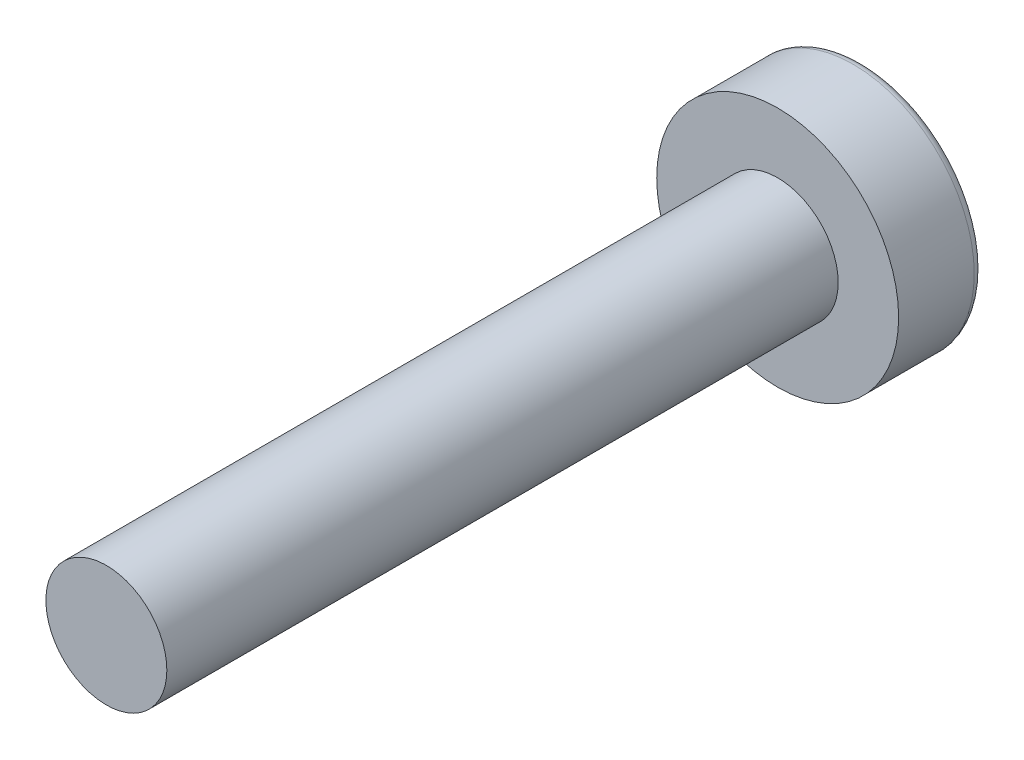
SolidWorks part; units mm, degrees
ref_plane "前视基准面" through (0, 0, 0) normal (0, 0, 1) x (1, 0, 0)
ref_plane "上视基准面" through (0, 0, 0) normal (0, 1, 0) x (1, 0, 0)
ref_plane "右视基准面" through (0, 0, 0) normal (1, 0, 0) x (0, 0, -1)
sketch "草图1" plane through (0, 0, 0) normal (0, 0, 1) x (1, 0, 0)
  circle A0 centre (0, 0) radius 4
  dimension "D1" = 8
extrude "凸台-拉伸1" add sketch "草图1" along normal blind 2.8
sketch "草图2" plane through (0, 0, 2.8) normal (0, 0, 1) x (1, 0, 0)
  circle A0 centre (0, 0) radius 2
  dimension "D1" = 4
extrude "凸台-拉伸2" add sketch "草图2" along normal blind 22.2
fillet "圆角1" radius 0.3 1 edges at (4, 0, 0)
